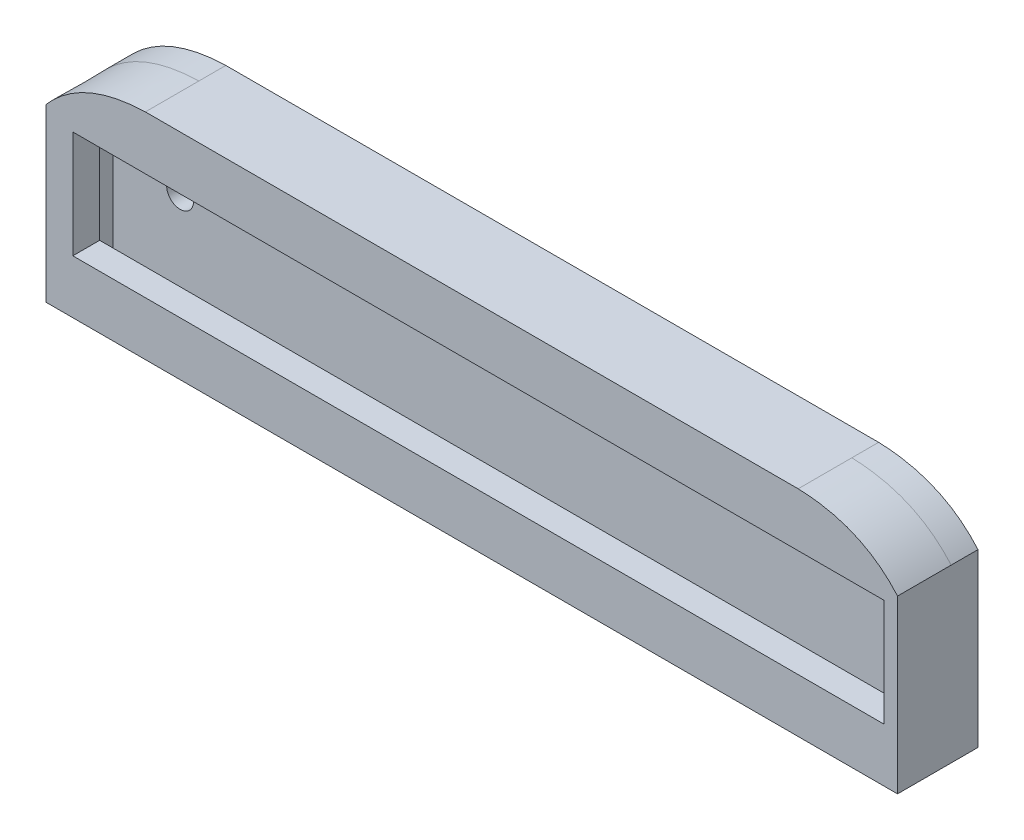
SolidWorks part; units mm, degrees
material "PE High Density"
ref_plane "Front Plane" through (0, 0, 0) normal (0, 0, 1) x (1, 0, 0)
ref_plane "Top Plane" through (0, 0, 0) normal (0, 1, 0) x (1, 0, 0)
ref_plane "Right Plane" through (0, 0, 0) normal (1, 0, 0) x (0, 0, -1)
sketch "Sketch1" plane through (0, 0, 0) normal (0, 0, 1) x (1, 0, 0)
  line L11 (-32.25, -8) -> (-32.25, 4.7772) construction
  line L12 (31.25, -8) -> (-32.25, -8) construction
  line L14 (23.8401, 8) -> (-24.8401, 8)
  line L16 (-32.25, -8) -> (-32.25, 4.7772)
  line L17 (31.25, -8) -> (-32.25, -8)
  line L18 (31.25, 4.7772) -> (31.25, -8)
  parabola Q0 (-24.8401, 8) -> (-32.25, 4.7772) focus (-28.1267, 2.6825) apex (-30.6319, 6.2449) construction
  parabola Q1 (23.8401, 8) -> (31.25, 4.7772) focus (27.1267, 2.6825) apex (29.6319, 6.2449) construction
  parabola Q2 (-24.8401, 8) -> (-32.25, 4.7772) focus (-28.1267, 2.6825) apex (-30.6319, 6.2449)
  parabola Q3 (23.8401, 8) -> (31.25, 4.7772) focus (27.1267, 2.6825) apex (29.6319, 6.2449)
  dimension "D1" = 63.5
extrude "Boss-Extrude1" add sketch "Sketch1" along normal blind 2
sketch "Sketch2" plane through (0, 0, 2) normal (0, 0, 1) x (1, 0, 0)
  line L13 (-32.25, -8) -> (31.25, -8)
  line L14 (-32.25, 4.7772) -> (-32.25, -8)
  line L15 (23.8401, 8) -> (-24.8401, 8)
  line L16 (31.25, -8) -> (31.25, 4.7772)
  line L19 (-32.25, -8) -> (31.25, -8)
  line L25 (-32.25, 4.7772) -> (-32.25, -8)
  line L26 (23.8401, 8) -> (-24.8401, 8)
  line L27 (31.25, -8) -> (31.25, 4.7772)
  line L35 (-31.25, -7) -> (30.25, -7)
  line L36 (-31.25, 4.3923) -> (-31.25, -7)
  line L37 (23.825, 7) -> (-24.825, 7)
  line L38 (30.25, -7) -> (30.25, 4.3923)
  line L39 (-31.25, -7) -> (30.25, -7)
  line L40 (-31.25, 4.3923) -> (-31.25, -7)
  line L41 (23.825, 7) -> (-24.825, 7)
  line L42 (30.25, -7) -> (30.25, 4.3923)
  parabola Q26 (-24.8401, 8) -> (-32.25, 4.7772) focus (-28.1267, 2.6825) apex (-30.6319, 6.2449)
  parabola Q27 (31.25, 4.7772) -> (23.8401, 8) focus (27.1267, 2.6825) apex (29.6319, 6.2449)
  parabola Q28 (-24.8401, 8) -> (-32.25, 4.7772) focus (-28.1267, 2.6825) apex (-30.6319, 6.2449)
  parabola Q29 (31.25, 4.7772) -> (23.8401, 8) focus (27.1267, 2.6825) apex (29.6319, 6.2449)
  spline S0 degree 3 poles (-695.2922, 3948.046) (128.5422, -279.2387) (19.7685, 15.0975) (-27.1693, 6.7187) (-27.7388, 6.5682) (-28.5742, 6.2508) (-28.8504, 6.129) (-29.3811, 5.8581) (-29.8934, 5.5592) (-30.3684, 5.2031) (-51.9753, -13.0315) (7.0875, -162.0334) (2853.5776, 2770.6819) knots -19.758046 -19.758046 -19.758046 -19.758046 0.25 0.25 0.5 0.5 0.625 0.625 0.75 0.875 0.875 12.591053 12.591053 12.591053 12.591053 only from (-24.825, 7) to (-31.25, 4.3923)
  spline S1 degree 3 poles (2658.0392, 2995.7268) (-1088.7994, -1840.5346) (116.4823, -52.8281) (28.4056, 5.8637) (27.8676, 6.1378) (26.7617, 6.561) (26.1898, 6.7143) (-17.8731, 14.6343) (-96.75, -247.7203) (1212.9192, 3825.3276) knots -44.315179 -44.315179 -44.315179 -44.315179 0.25 0.25 0.5 0.5 0.75 0.75 19.258172 19.258172 19.258172 19.258172 only from (30.25, 4.3923) to (23.825, 7)
  spline S2 degree 3 poles (-24.825, 7) (-25.4218, 6.9817) (-26.0108, 6.9255) (-27.1693, 6.7187) (-27.7388, 6.5682) (-28.5742, 6.2508) (-28.8504, 6.129) (-29.3811, 5.8581) (-29.8934, 5.5592) (-30.3684, 5.2031) (-30.8246, 4.8181) (-31.0435, 4.6107) (-31.25, 4.3923) knots 0 0 0 0 0.25 0.25 0.5 0.5 0.625 0.625 0.75 0.875 0.875 1 1 1 1
  spline S3 degree 3 poles (30.25, 4.3923) (29.8389, 4.8271) (29.3883, 5.2089) (28.4056, 5.8637) (27.8676, 6.1378) (26.7617, 6.561) (26.1898, 6.7143) (25.0153, 6.9254) (24.4216, 6.9817) (23.825, 7) knots 0 0 0 0 0.25 0.25 0.5 0.5 0.75 0.75 1 1 1 1
  dimension "D1" = 0
  dimension "D2" = 1
extrude "Boss-Extrude2" add sketch "Sketch2" along normal blind 2
sketch "Sketch4" plane through (0, 0, 4) normal (0, 0, 1) x (1, 0, 0)
  line L0 (30.25, -6) -> (30.25, 6) construction
  line L5 (-32.25, 8) -> (32.25, -8) construction
  line L6 (-32.25, -8) -> (32.25, 8) construction
  line L7 (-30.25, 4) -> (30.25, 4)
  line L8 (-30.25, 4) -> (-30.25, -4)
  line L9 (-30.25, -4) -> (30.25, -4)
  line L10 (30.25, 4) -> (30.25, -4)
  line L11 (-30.25, 4) -> (30.25, -4) construction
  line L12 (-30.25, -4) -> (30.25, 4) construction
  line L18 (-32.25, -8) -> (31.25, -8)
  line L19 (-32.25, 4.7772) -> (-32.25, -8)
  line L20 (23.8401, 8) -> (-24.8401, 8)
  line L21 (31.25, -8) -> (31.25, 4.7772)
  line L22 (-32.25, -8) -> (31.25, -8)
  line L23 (-32.25, 4.7772) -> (-32.25, -8)
  line L24 (23.8401, 8) -> (-24.8401, 8)
  line L25 (31.25, -8) -> (31.25, 4.7772)
  parabola Q2 (-24.8401, 8) -> (-32.25, 4.7772) focus (-28.1267, 2.6825) apex (-30.6319, 6.2449)
  parabola Q3 (31.25, 4.7772) -> (23.8401, 8) focus (27.1267, 2.6825) apex (29.6319, 6.2449)
  parabola Q4 (-24.8401, 8) -> (-32.25, 4.7772) focus (-28.1267, 2.6825) apex (-30.6319, 6.2449)
  parabola Q5 (31.25, 4.7772) -> (23.8401, 8) focus (27.1267, 2.6825) apex (29.6319, 6.2449)
  point P0 (0, 0)
  point P7 (0, 0)
  dimension "D3" = 4
  dimension "D2" = 0
extrude "Boss-Extrude3" add sketch "Sketch4" along normal blind 2
sketch "Sketch5" plane through (0, 0, 2) normal (0, 0, 1) x (1, 0, 0)
  line L0 (-32.25, 8) -> (-32.25, -8) construction
  line L1 (32.25, 8) -> (-32.25, 8) construction
  circle A0 centre (-26.25, 0) radius 1
  dimension "D1" = 2
  dimension "D2" = 6
  dimension "D3" = 8
extrude "Cut-Extrude1" cut sketch "Sketch5" against normal blind 1
sketch "Sketch6" plane through (0, 0, 0) normal (0, 0, -1) x (-1, 0, 0)
  line L8 (24.8401, 8) -> (31.25, 8)
  line L9 (31.25, 8) -> (32.25, 4.7772)
  parabola Q2 (24.8401, 8) -> (32.25, 4.7772) focus (28.1267, 2.6825) apex (30.6319, 6.2449) construction
  parabola Q3 (24.8401, 8) -> (32.25, 4.7772) focus (28.1267, 2.6825) apex (30.6319, 6.2449)
extrude "Cut-Extrude2" cut sketch "Sketch6" against normal up to next
mirror "Mirror1" about plane through (0, 0, 0) normal (1, 0, 0)
